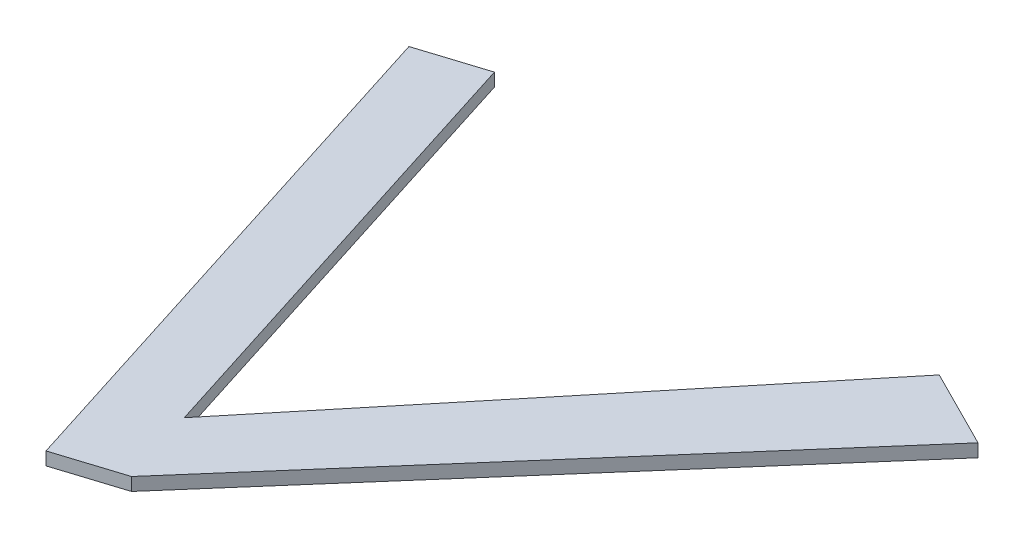
SolidWorks part; units mm, degrees
ref_plane "Front Plane" through (0, 0, 0) normal (0, 0, 1) x (1, 0, 0)
ref_plane "Top Plane" through (0, 0, 0) normal (0, 1, 0) x (1, 0, 0)
ref_plane "Right Plane" through (0, 0, 0) normal (1, 0, 0) x (0, 0, -1)
sketch "Sketch1" plane through (0, 0, 0) normal (0, 1, 0) x (1, 0, 0)
  line L0 (0, 0) -> (-11.1173, 35.0281)
  line L1 (-11.1173, 35.0281) -> (-16.1213, 33.4399)
  line L2 (-16.1213, 33.4399) -> (-3.1133, -7.5453)
  line L3 (-3.1133, -7.5453) -> (1.8907, -5.9572)
  line L4 (1.8907, -5.9572) -> (32.2686, 28.9176)
  line L5 (32.2686, 28.9176) -> (26.2413, 31.9565)
  line L6 (26.2413, 31.9565) -> (0, 0)
  dimension "D1" = 5.25
  dimension "D2" = 57
  dimension "D3" = 36.75
  dimension "D4" = 43
  dimension "D5" = 5.25
  dimension "D6" = 46.25
  dimension "D7" = 6.75
  dimension "D8" = 41.35
extrude "Boss-Extrude1" add sketch "Sketch1" along normal blind 1
